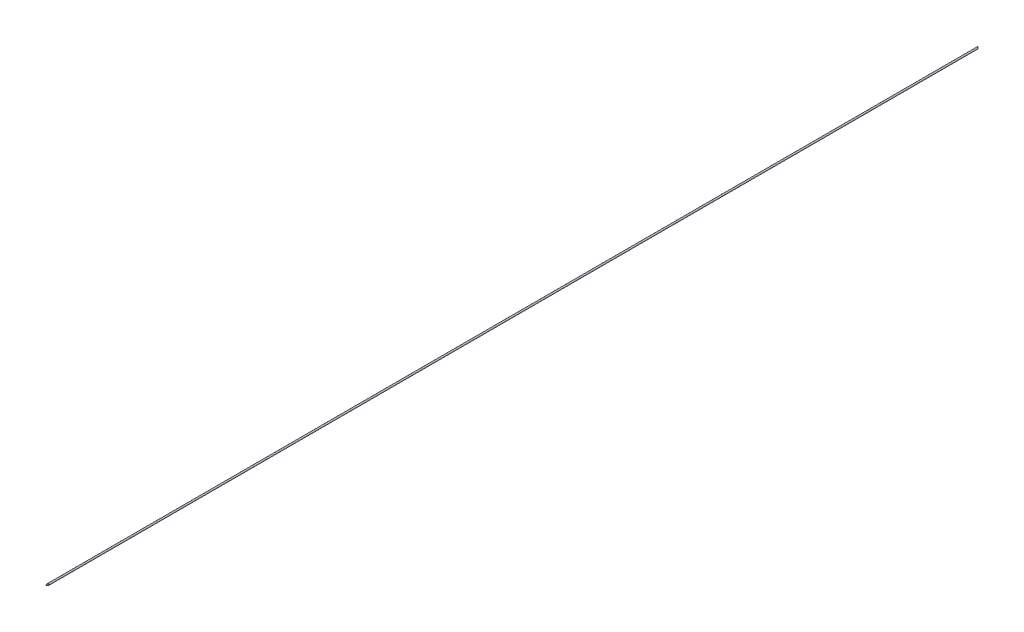
SolidWorks part; units mm, degrees
material "AISI 1015 Aço, trefilado (SS)"
ref_plane "Plano frontal" through (0, 0, 0) normal (0, 0, 1) x (1, 0, 0)
ref_plane "Plano superior" through (0, 0, 0) normal (0, 1, 0) x (1, 0, 0)
ref_plane "Plano direito" through (0, 0, 0) normal (1, 0, 0) x (0, 0, -1)
sketch "Esboço1" plane through (0, 0, 0) normal (0, 0, 1) x (1, 0, 0)
  circle A0 centre (0, 0) radius 5
  dimension "D1" = 10
extrude "Ressalto-extrusão1" add sketch "Esboço1" along normal mid plane 5840 contours A0
sketch "Esboço2" plane through (0, 0, 0) normal (0, 1, 0) x (1, 0, 0)
  line L0 (-5, -2920) -> (5, -2920) construction
  line L1 (-5, -2920) -> (5, -2920)
  line L5 (-5, -2920) -> (5, -2910)
  line L6 (5, -2920) -> (5, 2920) construction
  line L7 (5, -2910) -> (5, -2920)
  dimension "D2" = 45
extrude "Corte-extrusão1" cut sketch "Esboço2" against normal mid plane 10
mirror "Espelhar1" about plane through (0, 0, 0) normal (0, 0, 1) of "Corte-extrusão1"
